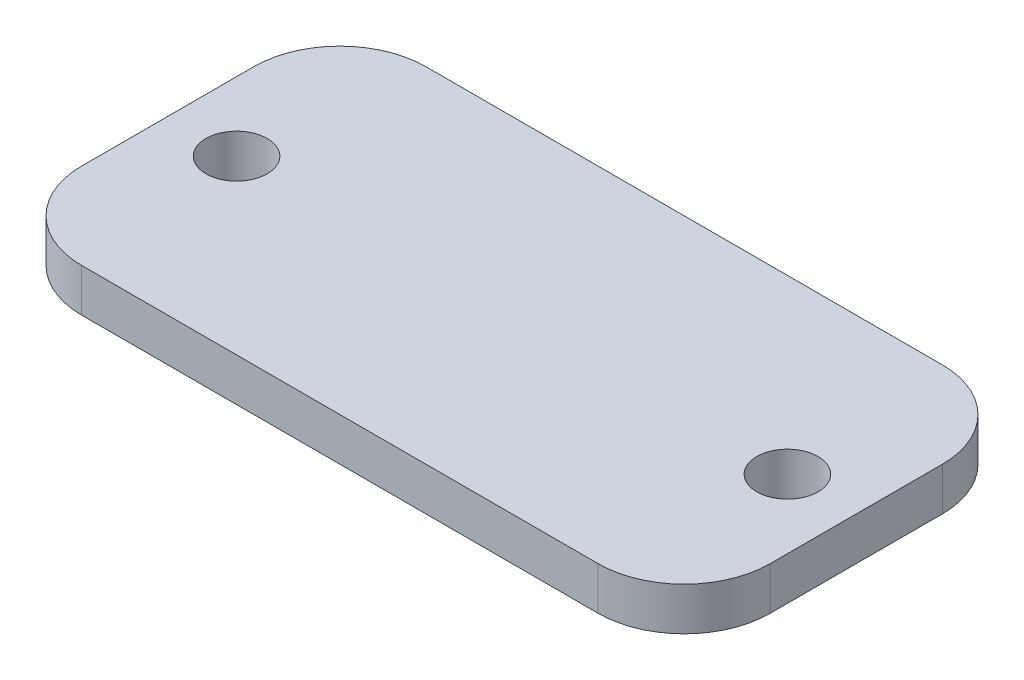
SolidWorks part; units mm, degrees
ref_plane "Front Plane" through (0, 0, 0) normal (0, 0, 1) x (1, 0, 0)
ref_plane "Top Plane" through (0, 0, 0) normal (0, 1, 0) x (1, 0, 0)
ref_plane "Right Plane" through (0, 0, 0) normal (1, 0, 0) x (0, 0, -1)
sketch "Sketch1" plane through (0, 0, 0) normal (0, 1, 0) x (1, 0, 0)
  line L1 (0, 0) -> (25.4, 0)
  line L2 (0, 0) -> (0, 12.7)
  line L3 (0, 12.7) -> (25.4, 12.7)
  line L4 (25.4, 0) -> (25.4, 12.7)
  dimension "D1" = 12.7
  dimension "D2" = 25.4
extrude "Boss-Extrude1" add sketch "Sketch1" along normal blind 1.5875
fillet "Fillet1" radius 3.175 4 edges at (25.4, 0.7937, 0) (25.4, 0.7937, -12.7) (0, 0.7937, -12.7) (0, 0.7937, 0)
sketch "Sketch2" plane through (0, 1.5875, 0) normal (0, 1, 0) x (1, 0, 0)
  line L0 (12.7, 12.7) -> (12.7, 0) construction
  line L1 (22.225, 12.7) -> (3.175, 12.7) construction
  line L2 (3.175, 0) -> (22.225, 0) construction
  line L3 (12.7, 0) -> (25.4, 6.35) construction
  line L4 (25.4, 3.175) -> (25.4, 9.525) construction
  line L5 (25.4, 6.35) -> (0, 6.35) construction
  line L6 (0, 9.525) -> (0, 3.175) construction
  circle A0 centre (2.54, 6.35) radius 1.1303
  circle A1 centre (22.86, 6.35) radius 1.1303
  dimension "D1" = 2.2606
  dimension "D2" = 10.16
extrude "Cut-Extrude1" cut sketch "Sketch2" against normal through all
